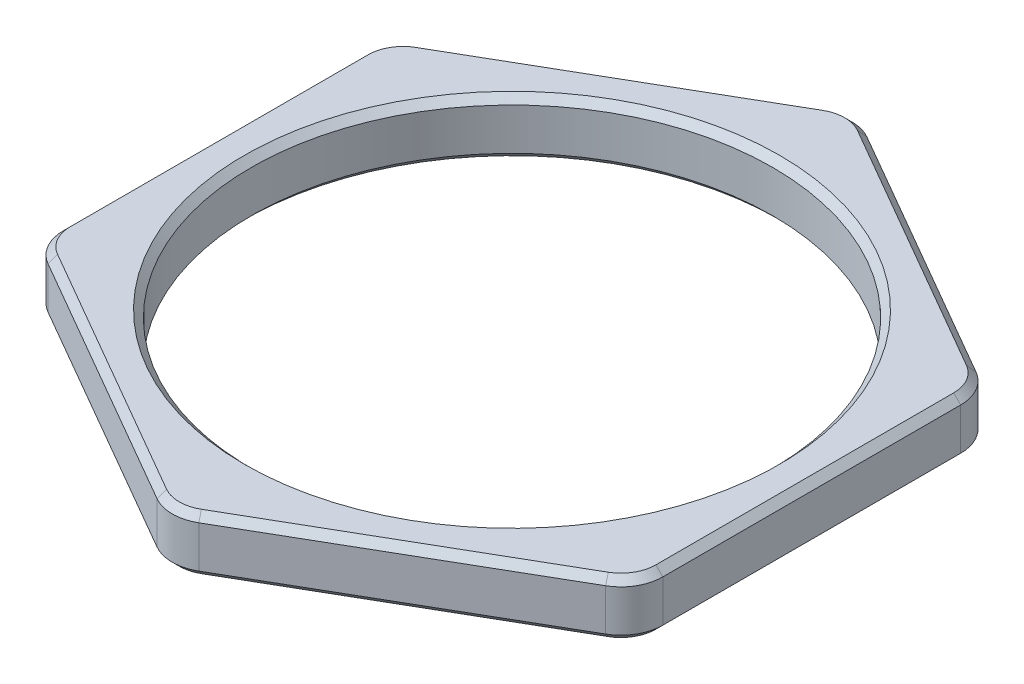
SolidWorks part; units mm, degrees
material "Plain Carbon Steel"
ref_plane "Front Plane" through (0, 0, 0) normal (0, 0, 1) x (1, 0, 0)
ref_plane "Top Plane" through (0, 0, 0) normal (0, 1, 0) x (1, 0, 0)
ref_plane "Right Plane" through (0, 0, 0) normal (1, 0, 0) x (0, 0, -1)
sketch "Sketch1" plane through (0, 0, 0) normal (0, 1, 0) x (1, 0, 0)
  line L1 (-1.5, 23.96) -> (-20, 13.2791)
  line L2 (-21.5, 10.681) -> (-21.5, -10.681)
  line L3 (-20, -13.2791) -> (-1.5, -23.96)
  line L4 (1.5, -23.96) -> (20, -13.2791)
  line L5 (21.5, -10.681) -> (21.5, 10.681)
  line L6 (20, 13.2791) -> (1.5, 23.96)
  circle A0 centre (0, 0) radius 21.5 construction
  circle A1 centre (0, 0) radius 18.695
  arc A2 (-1.5, 23.96) -> (1.5, 23.96) centre (0, 21.362) cw
  arc A3 (21.5, 10.681) -> (20, 13.2791) centre (18.5, 10.681) ccw
  arc A4 (20, -13.2791) -> (21.5, -10.681) centre (18.5, -10.681) ccw
  arc A5 (-1.5, -23.96) -> (1.5, -23.96) centre (0, -21.362) ccw
  arc A6 (-21.5, -10.681) -> (-20, -13.2791) centre (-18.5, -10.681) ccw
  arc A7 (-20, 13.2791) -> (-21.5, 10.681) centre (-18.5, 10.681) ccw
  dimension "D1" = 3
  dimension "D2" = 43
extrude "Boss-Extrude1" add sketch "Sketch1" along normal blind 4
chamfer "Chamfer1" distance 0.5 angle 45 26 edges at (0, 0, 18.695) (-10.75, 0, -18.6195) (-21.0981, 0, -12.181) (-21.5, 0, 0) (-21.0981, 0, 12.181) (-10.75, 0, 18.6195) (0, 0, 24.362) (10.75, 0, 18.6195) (21.0981, 0, 12.181) (21.5, 0, 0) (21.0981, 0, -12.181) (10.75, 0, -18.6195) (0, 0, -24.362) (0, 4, 18.695) (10.75, 4, -18.6195) (21.0981, 4, -12.181) (21.5, 4, 0) (21.0981, 4, 12.181) (10.75, 4, 18.6195) (0, 4, 24.362) (-10.75, 4, 18.6195) (-21.0981, 4, 12.181) (-21.5, 4, 0) (-21.0981, 4, -12.181) (-10.75, 4, -18.6195) (0, 4, -24.362)
